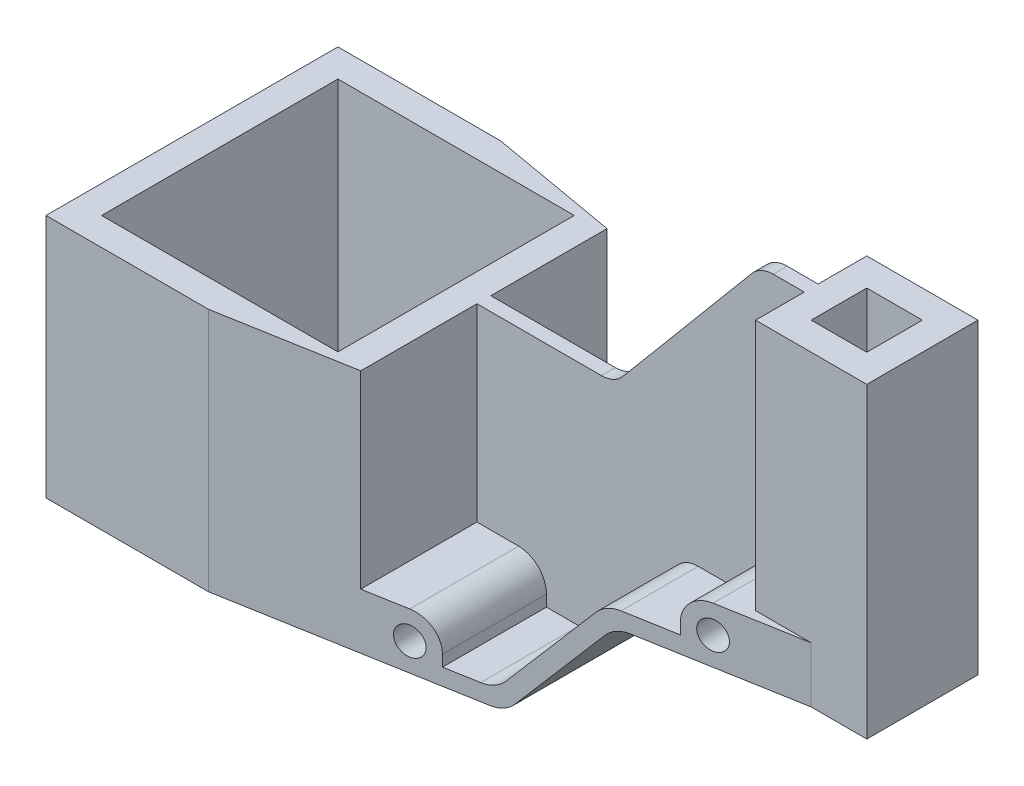
SolidWorks part; units mm, degrees
material "Alliage 1060"
ref_plane "Front Plane" through (0, 0, 0) normal (0, 0, 1) x (1, 0, 0)
ref_plane "Top Plane" through (0, 0, 0) normal (0, 1, 0) x (1, 0, 0)
ref_plane "Right Plane" through (0, 0, 0) normal (1, 0, 0) x (0, 0, -1)
sketch "Esquisse1" plane through (0, 0, 0) normal (0, 1, 0) x (1, 0, 0)
  line L0 (0, 0) -> (251.0912, 0) construction
  line L1 (-52.5, 52.5) -> (52.5, 52.5)
  line L2 (-52.5, 52.5) -> (-52.5, -52.5)
  line L3 (-52.5, -52.5) -> (52.5, -52.5)
  line L4 (52.5, 52.5) -> (52.5, -52.5)
  line L10 (-42.5, 42.5) -> (42.5, 42.5)
  line L11 (42.5, 42.5) -> (42.5, -42.5)
  line L12 (-42.5, -42.5) -> (42.5, -42.5)
  line L13 (-42.5, 42.5) -> (-42.5, -42.5)
  dimension "D1" = 52.5
  dimension "D2" = 52.5
  dimension "D3" = 105
  dimension "D4" = 52.5
  dimension "D9" = 10
extrude "Boss.-Extru.3" add sketch "Esquisse1" along normal blind 88
sketch "Esquisse3" plane through (0, 0, 52.5) normal (0, 0, 1) x (1, 0, 0)
  line L0 (52.5, 0) -> (96.6584, 0)
  line L1 (96.6584, 0) -> (130.2224, 40)
  line L2 (130.2224, 40) -> (190.2224, 40)
  line L3 (52.5, 6) -> (93.8606, 6)
  line L4 (93.8606, 6) -> (127.4246, 46)
  line L5 (127.4246, 46) -> (190.2224, 46)
  line L6 (190.2224, 46) -> (190.2224, 40)
  dimension "D1" = 6
  dimension "D2" = 130
  dimension "D3" = 40
  dimension "D4" = 60
extrude "Boss.-Extru.4" add sketch "Esquisse3" against normal up to surface (105 mm away) contours L6 L5 L4 L3 L0 L1 L2 up to face at (0, 44, -52.5)
sketch "Esquisse7" plane through (0, 40, 0) normal (0, -1, 0) x (1, 0, 0)
  line L0 (0, 0) -> (190.2224, 0) construction
  line L1 (190.2224, -52.5) -> (190.2224, 52.5) construction
  line L2 (180.2224, 10) -> (180.2224, -10)
  line L3 (170.2224, 20) -> (210.2224, 20)
  line L4 (170.2224, 20) -> (170.2224, -20)
  line L5 (170.2224, -20) -> (210.2224, -20)
  line L6 (210.2224, 20) -> (210.2224, -20)
  line L7 (170.2224, 20) -> (210.2224, -20) construction
  line L8 (170.2224, -20) -> (210.2224, 20) construction
  line L9 (180.2224, -10) -> (200.2224, -10)
  line L10 (200.2224, 10) -> (200.2224, -10)
  line L11 (180.2224, 10) -> (200.2224, 10)
  dimension "D1" = 40
  dimension "D2" = 40
  dimension "D3" = 10
extrude "Boss.-Extru.11" add sketch "Esquisse7" against normal blind 110.5
sketch "Esquisse13" plane through (0, 46, 0) normal (0, 1, 0) x (1, 0, 0)
  line L4 (180.2224, -10) -> (190.2224, -10)
  line L21 (180.2224, -10) -> (190.2224, -10)
  line L26 (190.2224, -10) -> (190.2224, 10)
  line L28 (190.2224, -10) -> (190.2224, 10)
  line L30 (190.2224, 10) -> (180.2224, 10)
  line L31 (190.2224, 10) -> (180.2224, 10)
  line L32 (180.2224, 10) -> (180.2224, -10)
  line L33 (180.2224, 10) -> (180.2224, -10)
  dimension "D1" = 0
extrude "Enlèv. mat.-Extru.9" cut sketch "Esquisse13" against normal up to next
sketch "Esquisse14" plane through (0, 0, 0) normal (0, 0, 1) x (1, 0, 0)
  line L0 (52.5, 88) -> (101.9653, 88)
  line L1 (101.9653, 88) -> (154.409, 150.5)
  line L2 (154.409, 150.5) -> (170.2224, 150.5)
  line L8 (93.8606, 6) -> (127.4246, 46) construction
  line L9 (52.5, 6) -> (93.8606, 6) construction
  line L10 (127.4246, 46) -> (170.2224, 46)
  line L15 (93.8606, 6) -> (127.4246, 46)
  line L16 (52.5, 6) -> (93.8606, 6)
  line L17 (170.2224, 46) -> (170.2224, 150.5)
  line L18 (52.5, 88) -> (52.5, 6)
  dimension "D1" = 46.5
extrude "Boss.-Extru.12" add sketch "Esquisse14" along normal mid plane 5
sketch "Esquisse17" plane through (0, 0, 0) normal (0, 0, 1) x (1, 0, 0)
  line L0 (-52.5, 88) -> (-52.5, 0) construction
  line L1 (-52.5, 0) -> (96.6584, 0) construction
  line L2 (210.2224, 150.5) -> (210.2224, 40) construction
  line L3 (130.2224, 40) -> (190.2224, 40) construction
  line L7 (44, 20) -> (44, 0)
  line L8 (44, 0) -> (77.5, 0)
  line L9 (77.5, 0) -> (77.5, 6)
  line L15 (190.2224, 40) -> (150.2224, 40)
  line L30 (52.5, 6) -> (93.8606, 6) construction
  line L36 (190.2224, 40) -> (190.2224, 60)
  line L37 (190.2224, 60) -> (150.2224, 60)
  line L38 (150.2224, 40) -> (150.2224, 60)
  line L39 (44, 20) -> (77.5, 20)
  line L42 (77.5, 20) -> (77.5, 6)
  circle A0 centre (67.5, 10) radius 5
  circle A1 centre (160.2224, 50) radius 5
  dimension "D9" = 10
  dimension "D2" = 10
  dimension "D3" = 120
  dimension "D4" = 10
  dimension "D5" = 50
  dimension "D6" = 10
  dimension "D7" = 10
  dimension "D8" = 10
  dimension "D10" = 20
extrude "Boss.-Extru.13" add sketch "Esquisse17" along normal mid plane 105
sketch "Esquisse18" plane through (0, 0, 2.5) normal (0, 0, 1) x (1, 0, 0)
  circle A1 centre (160.2224, 50) radius 5
  circle A2 centre (160.2224, 50) radius 5
  circle A3 centre (67.5, 10) radius 5
  circle A4 centre (67.5, 10) radius 5
  dimension "D1" = 0
  dimension "D2" = 0
extrude "Enlèv. mat.-Extru.12" cut sketch "Esquisse18" against normal through all both and the other way through all
sketch "Esquisse19" plane through (0, 60, 0) normal (0, 1, 0) x (1, 0, 0)
  line L4 (180.2224, 10) -> (180.2224, -10)
  line L5 (180.2224, -10) -> (190.2224, -10)
  line L6 (190.2224, -10) -> (190.2224, 10)
  line L7 (190.2224, 10) -> (180.2224, 10)
  line L8 (180.2224, 10) -> (180.2224, -10)
  line L9 (180.2224, -10) -> (190.2224, -10)
  line L10 (190.2224, -10) -> (190.2224, 10)
  line L11 (190.2224, 10) -> (180.2224, 10)
  dimension "D1" = 0
extrude "Enlèv. mat.-Extru.13" cut sketch "Esquisse19" against normal up to next
sketch "Esquisse20" plane through (0, 0, 0) normal (0, 1, 0) x (1, 0, 0)
  line L1 (52.5, 52.5) -> (-52.5, 52.5) construction
  line L2 (6, 52.5) -> (190.2224, 20)
  line L3 (170.2224, 20) -> (210.2224, 20) construction
  line L4 (190.2224, 20) -> (210.2224, 20)
  line L6 (210.2224, -20) -> (190.2224, -20)
  line L7 (190.2224, -20) -> (6, -52.5)
  line L8 (6, 52.5) -> (210.2224, 52.5)
  line L9 (210.2224, 52.5) -> (210.2224, 20)
  line L11 (6, -52.5) -> (210.2224, -52.5)
  line L12 (210.2224, -52.5) -> (210.2224, -20)
  line L13 (-52.5, -52.5) -> (52.5, -52.5) construction
  point P1 (0, 0)
  point P14 (0, 0)
fillet "Congé1" radius 10 12 edges at (77.5, 20, -27.5) (93.8606, 6, -27.5) (127.4246, 46, -27.5) (150.2224, 60, -27.5) (96.6584, 0, 0) (130.2224, 40, 0) (150.2224, 60, 27.5) (77.5, 20, 27.5) (93.8606, 6, 27.5) (127.4246, 46, 27.5) (154.409, 150.5, 0) (101.9653, 88, 0)
extrude "Enlèv. mat.-Extru.15" cut sketch "Esquisse20" along normal up to surface (150.5 mm away)
equation "\"A\" = 210'a"
equation "\"B\"= 105'b"
equation "\"W\"= \"B\" / 2'w"
equation "\"X\"= \"A\" / 4'x"
equation "\"Y\"= \"B\" + 5.5'y"
equation "\"Z\"= \"B\" + 15'z"
equation "\"C\"= 40"
equation "\"D1@Esquisse1\"=\"X\""
equation "\"D2@Esquisse1\"=\"X\""
equation "\"D3@Esquisse1\"=\"B\""
equation "\"D4@Esquisse1\"=\"W\""
equation "\"D1@Boss.-Extru.11\"=\"Y\""
equation "\"D1@Esquisse14\"=\"X\"-6"
equation "\"D3@Esquisse17\"=\"Z\""
equation "\"D1@Boss.-Extru.13\"=\"X\"*2"
equation "\"D1@Enlèv. mat.-Extru.12\"=\"X\"+\"X\""
